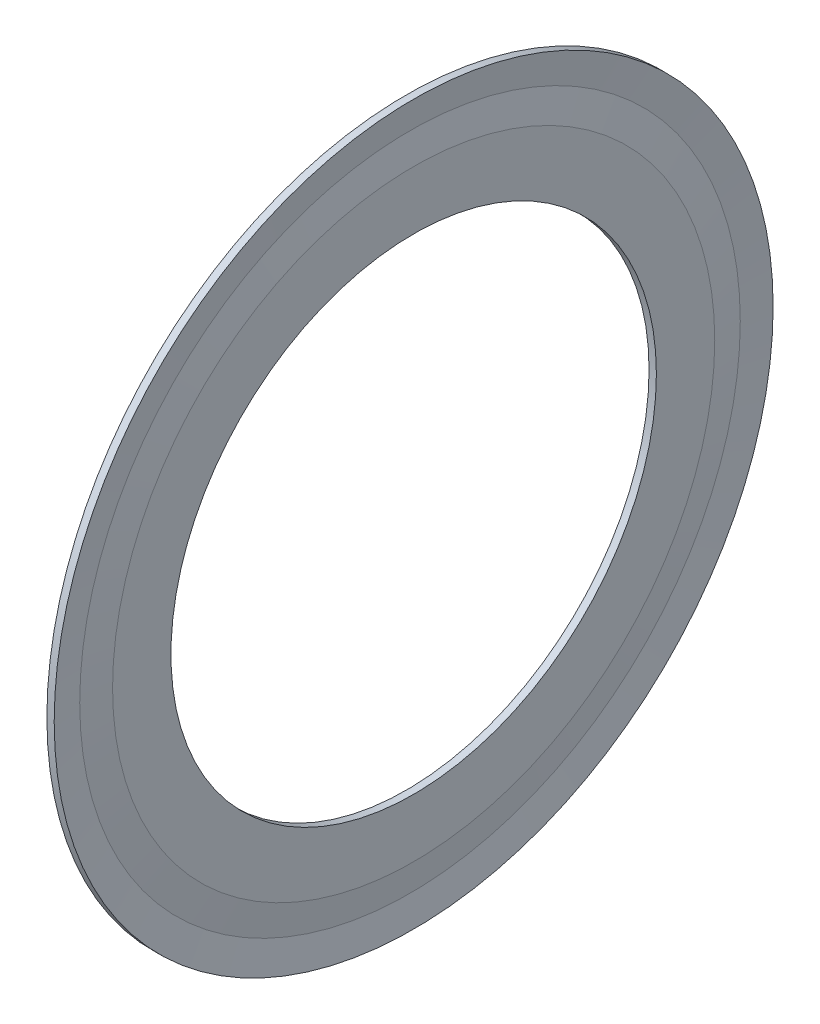
SolidWorks part; units mm, degrees
ref_plane "Front Plane" through (0, 0, 0) normal (0, 0, 1) x (1, 0, 0)
ref_plane "Top Plane" through (0, 0, 0) normal (0, 1, 0) x (1, 0, 0)
ref_plane "Right Plane" through (0, 0, 0) normal (1, 0, 0) x (0, 0, -1)
ref_plane "Plane1" through (0, 0, 0) normal (0, 0, 1) x (1, 0, 0)
sketch "Sketch1" plane through (0, 0, 0) normal (0, 0, 1) x (1, 0, 0)
  line L0 (4.4042, 4.9) -> (4.5234, 3.95)
  line L1 (4.5234, 3.95) -> (4.6425, 3.95)
  line L2 (4.6425, 3.95) -> (4.6425, 4.9)
  line L3 (4.6425, 4.9) -> (4.583, 5.375)
  line L4 (4.583, 5.375) -> (4.6425, 5.85)
  line L5 (4.6425, 5.85) -> (4.5234, 5.85)
  line L6 (4.5234, 5.85) -> (4.4042, 5.3526)
  line L7 (4.4042, 5.3526) -> (4.4042, 4.9)
  line L8 (50, 0) -> (-50, 0) construction
revolve "Revolve1" add sketch "Sketch1" angle 360 about L8
